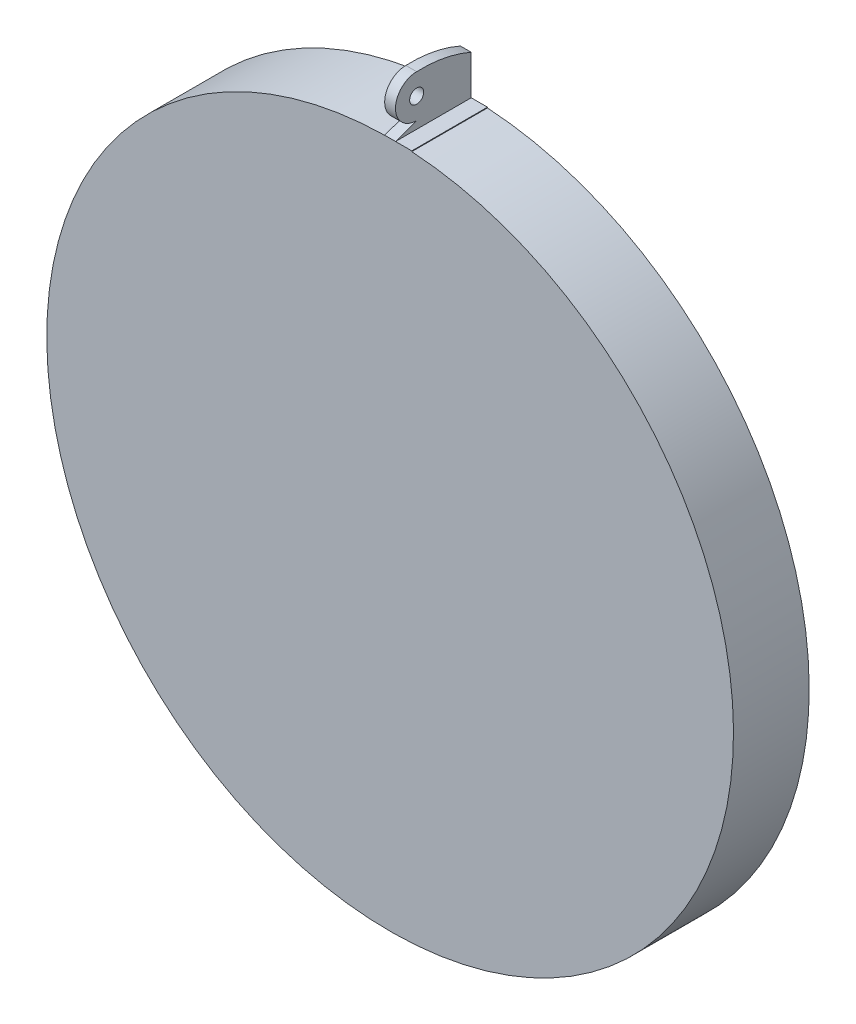
SolidWorks part; units mm, degrees
ref_plane "Front Plane" through (0, 0, 0) normal (0, 0, 1) x (1, 0, 0)
ref_plane "Top Plane" through (0, 0, 0) normal (0, 1, 0) x (1, 0, 0)
ref_plane "Right Plane" through (0, 0, 0) normal (1, 0, 0) x (0, 0, -1)
sketch "Sketch1" plane through (0, 0, 0) normal (0, 0, 1) x (1, 0, 0)
  circle A0 centre (0, 0) radius 63.5
  dimension "D1" = 127
extrude "Boss-Extrude2" add sketch "Sketch1" along normal blind 23
shell "Shell4" thickness 3
sketch "Sketch4" plane through (0, 0, 20) normal (0, 0, -1) x (-1, 0, 0)
  circle A0 centre (0, 0) radius 56.097
extrude "Cut-Extrude1" cut sketch "Sketch4" against normal blind 22
sketch "Sketch8" plane through (0, 0, 0) normal (1, 0, 0) x (0, 0, -1)
  line L0 (-23, 63.5) -> (0, 63.5)
  arc A0 (-19.0928, 72.7285) -> (-19.0928, 64.8949) centre (-19.0928, 68.8117) ccw
  circle A1 centre (-19.0928, 68.8117) radius 1.3
  arc A2 (-19.0928, 72.7285) -> (0, 63.5) centre (-18.1616, 50.2902) cw
  arc A3 (-19.0928, 64.8949) -> (-23, 63.5) centre (37.5589, -99.9637) ccw
  dimension "D1" = 2.6
extrude "Boss-Extrude6" add sketch "Sketch8" along normal blind 1 and the other way blind 1 separate body
sketch "Sketch9" plane through (0, 63.5, 0) normal (0, -1, 0) x (1, 0, 0)
  line L1 (-1, 23) -> (4, 23)
  line L2 (-1, 23) -> (-1, 0)
  line L3 (-1, 0) -> (4, 0)
  line L4 (4, 23) -> (4, 0)
extrude "Boss-Extrude7" add sketch "Sketch9" along normal up to surface (0.1261 mm away)
sketch "Sketch11" plane through (0, 0, 0) normal (0, 0, -1) x (-1, 0, 0)
  circle A0 centre (0, 0) radius 63.5
extrude "Cut-Extrude2" cut sketch "Sketch11" against normal blind 9
sketch "Sketch12" plane through (0, 0, 9) normal (0, 0, -1) x (-1, 0, 0)
  line L1 (-8.4028, 62.9416) -> (11.0774, 62.9416)
  line L2 (-8.4028, 62.9416) -> (-8.4028, 75.1639)
  line L3 (-8.4028, 75.1639) -> (11.0774, 75.1639)
  line L4 (11.0774, 62.9416) -> (11.0774, 75.1639)
  arc A0 (-4, 63.3739) -> (1, 63.4921) centre (0, 0) ccw construction
extrude "Cut-Extrude3" cut sketch "Sketch12" along normal blind 13
sketch "Sketch13" plane through (0, 0, 23) normal (0, 0, 1) x (1, 0, 0)
  circle A0 centre (0, 0) radius 63.5
extrude "Boss-Extrude8" add sketch "Sketch13" against normal blind 2
